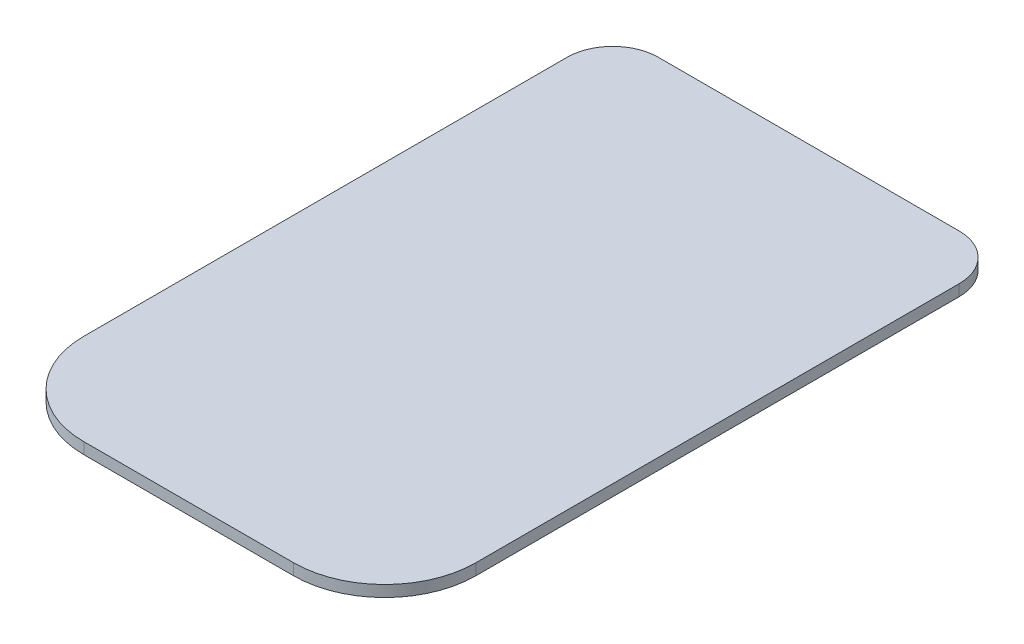
SolidWorks part; units mm, degrees
ref_plane "Front Plane" through (0, 0, 0) normal (0, 0, 1) x (1, 0, 0)
ref_plane "Top Plane" through (0, 0, 0) normal (0, 1, 0) x (1, 0, 0)
ref_plane "Right Plane" through (0, 0, 0) normal (1, 0, 0) x (0, 0, -1)
sketch "Sketch1" plane through (0, 0, 0) normal (0, 1, 0) x (1, 0, 0)
  line L1 (12.7, 0) -> (41.91, 0)
  line L2 (0, 12.7) -> (0, 80.01)
  line L3 (6.35, 86.36) -> (48.26, 86.36)
  line L4 (54.61, 12.7) -> (54.61, 80.01)
  arc A0 (54.61, 80.01) -> (48.26, 86.36) centre (48.26, 80.01) ccw
  arc A1 (0, 80.01) -> (6.35, 86.36) centre (6.35, 80.01) cw
  arc A2 (12.7, 0) -> (0, 12.7) centre (12.7, 12.7) cw
  arc A3 (54.61, 12.7) -> (41.91, 0) centre (41.91, 12.7) cw
  point P7 (54.61, 86.36)
  point P10 (0, 86.36)
  point P13 (0, 0)
  point P16 (54.61, 0)
  dimension "D3" = 6.35
  dimension "D4" = 6.35
  dimension "D5" = 12.7
  dimension "D6" = 12.7
  dimension "D1" = 54.61
  dimension "D2" = 86.36
extrude "Boss-Extrude1" add sketch "Sketch1" along normal blind 1.5748
